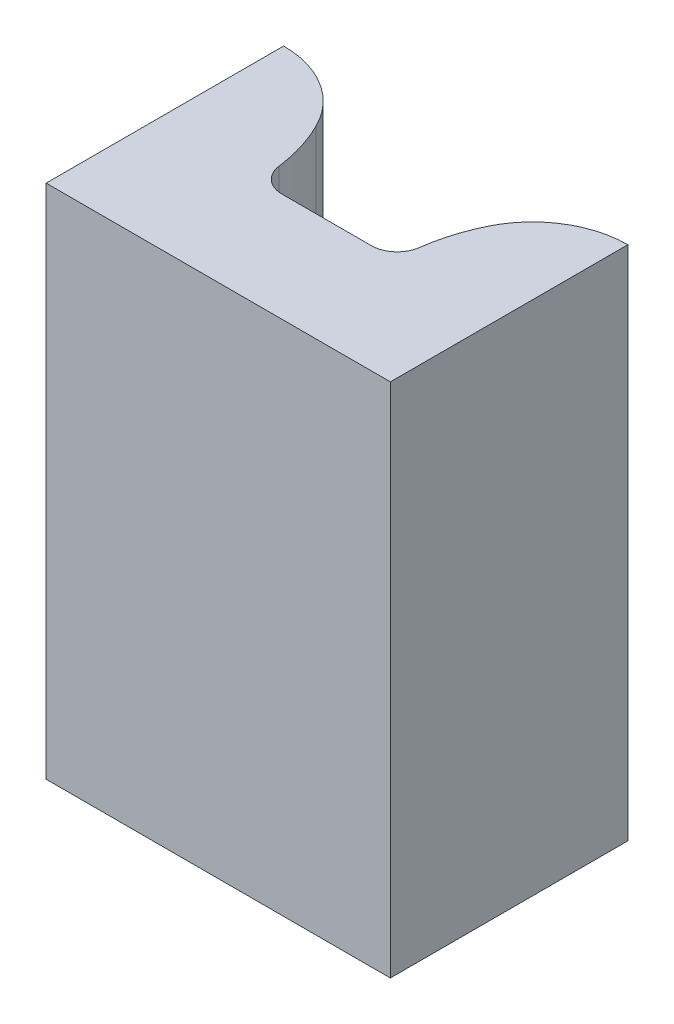
SolidWorks part; units mm, degrees
ref_plane "Płaszczyzna przednia" through (0, 0, 0) normal (0, 0, 1) x (1, 0, 0)
ref_plane "Płaszczyzna górna" through (0, 0, 0) normal (0, 1, 0) x (1, 0, 0)
ref_plane "Płaszczyzna prawa" through (0, 0, 0) normal (1, 0, 0) x (0, 0, -1)
sketch "Sketch1" plane through (0, 0, 0) normal (0, 1, 0) x (1, 0, 0)
  line L0 (0, 0) -> (2, 0)
  line L1 (0, 0) -> (0, 1.38)
  line L2 (2, 0) -> (2, 1.38)
  line L3 (0, 0.376) -> (2, 0.376) construction
  line L4 (-0.4, 0.63) -> (2.4, 0.63) construction
  line L5 (2.4, 1.38) -> (2.4, 0) construction
  line L6 (-0.4, 1.38) -> (-0.4, 0) construction
  line L7 (2, 0.825) -> (0, 0.825) construction
  line L8 (1, 0) -> (1, 1.5077) construction
  line L9 (0.7402, 0.63) -> (1.2598, 0.63)
  arc A0 (1.5011, 1.0682) -> (1.4085, 0.7604) centre (2.4, 0.63) ccw
  arc A1 (0.5915, 0.7604) -> (0.4989, 1.0682) centre (-0.4, 0.63) ccw
  arc A2 (2, 1.38) -> (1.5011, 1.0682) centre (2, 0.825) ccw
  arc A4 (0.5915, 0.7604) -> (0.7402, 0.63) centre (0.7402, 0.78) ccw
  arc A5 (1.4085, 0.7604) -> (1.2598, 0.63) centre (1.2598, 0.78) cw
  arc A6 (0.4989, 1.0682) -> (0, 1.38) centre (0, 0.825) ccw
  dimension "D6" = 2
  dimension "D8" = 2
  dimension "D9" = 1.11
  dimension "D12" = 0.3
  dimension "D1" = 2
  dimension "D2" = 1.38
  dimension "D3" = 1.004
  dimension "D4" = 0.254
  dimension "D5" = 0.4
  dimension "D7" = 0.4
  dimension "D10" = 0.555
extrude "Boss-Extrude1" add sketch "Sketch1" along normal mid plane 3
